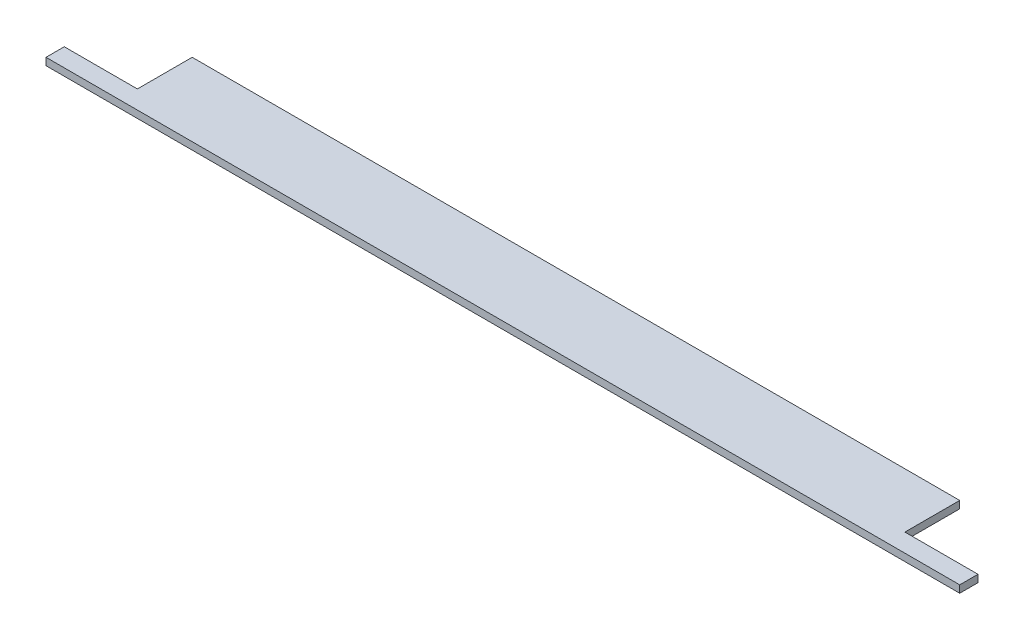
SolidWorks part; units mm, degrees
ref_plane "Front Plane" through (0, 0, 0) normal (0, 0, 1) x (1, 0, 0)
ref_plane "Top Plane" through (0, 0, 0) normal (0, 1, 0) x (1, 0, 0)
ref_plane "Right Plane" through (0, 0, 0) normal (1, 0, 0) x (0, 0, -1)
sketch "Эскиз1" plane through (0, 0, 0) normal (0, 1, 0) x (1, 0, 0)
  line L1 (0, 0) -> (500, 0)
  line L2 (0, 0) -> (0, 40)
  line L3 (0, 40) -> (500, 40)
  line L4 (500, 0) -> (500, 40)
  dimension "D1" = 40
  dimension "D2" = 500
extrude "Бобышка-Вытянуть1" add sketch "Эскиз1" along normal blind 4
sketch "Эскиз3" plane through (0, 4, 0) normal (0, 1, 0) x (1, 0, 0)
  line L0 (0, 10) -> (40, 10)
  line L1 (0, 40) -> (0, 0) construction
  line L2 (40, 10) -> (40, 40)
  line L3 (500, 40) -> (0, 40) construction
  line L4 (40, 40) -> (0, 40)
  line L5 (0, 40) -> (0, 10)
  dimension "D1" = 40
  dimension "D2" = 30
extrude "Вырез-Вытянуть1" cut sketch "Эскиз3" against normal through all
sketch "Эскиз4" plane through (0, 4, 0) normal (0, 1, 0) x (1, 0, 0)
  line L0 (460, 40) -> (460, 10)
  line L1 (500, 40) -> (40, 40) construction
  line L2 (460, 10) -> (500, 10)
  line L3 (500, 0) -> (500, 40) construction
  line L4 (500, 10) -> (500, 40)
  line L5 (500, 40) -> (460, 40)
  dimension "D1" = 40
  dimension "D2" = 30
extrude "Вырез-Вытянуть2" cut sketch "Эскиз4" against normal through all
